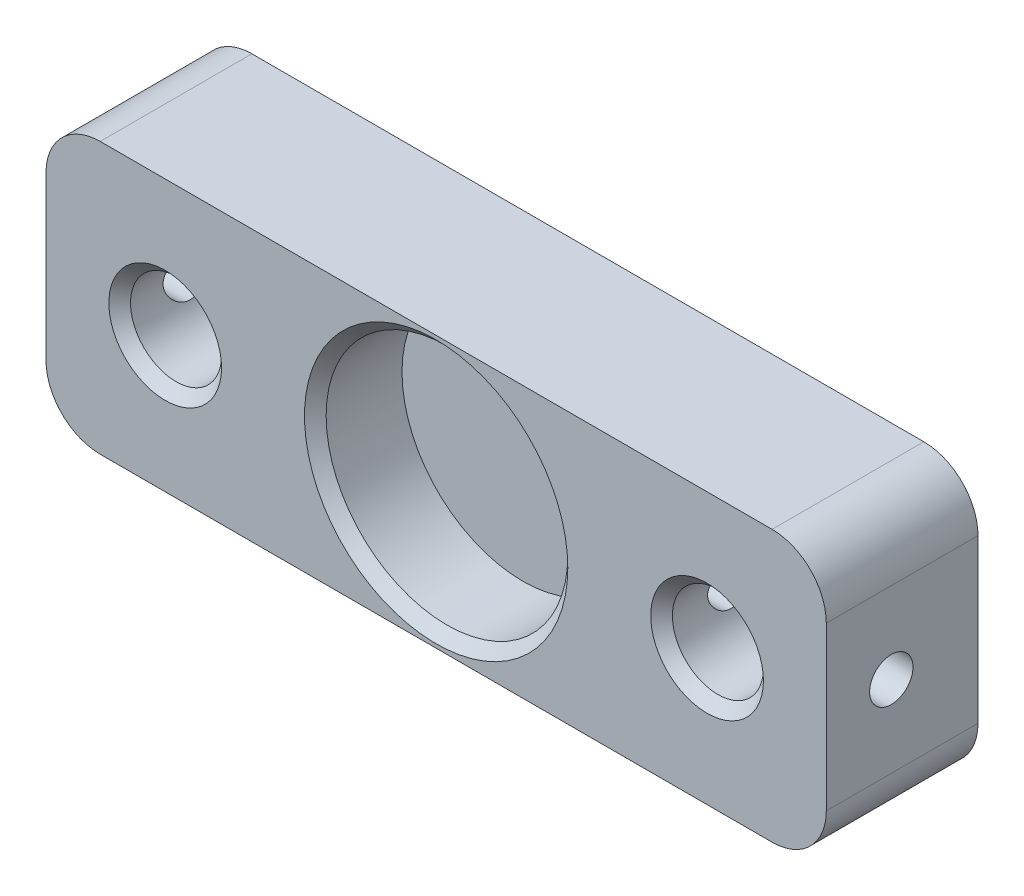
SolidWorks part; units mm, degrees
ref_plane "Płaszczyzna przednia" through (0, 0, 0) normal (0, 0, 1) x (1, 0, 0)
ref_plane "Płaszczyzna górna" through (0, 0, 0) normal (0, 1, 0) x (1, 0, 0)
ref_plane "Płaszczyzna prawa" through (0, 0, 0) normal (1, 0, 0) x (0, 0, -1)
sketch "Sketch1" plane through (0, 0, 0) normal (0, 0, 1) x (1, 0, 0)
  line L1 (-36, 12.5) -> (36, 12.5)
  line L2 (-36, 12.5) -> (-36, -12.5)
  line L3 (-36, -12.5) -> (36, -12.5)
  line L4 (36, 12.5) -> (36, -12.5)
  line L5 (-36, 12.5) -> (36, -12.5) construction
  line L6 (-36, -12.5) -> (36, 12.5) construction
  point P140 (0, 0)
  dimension "D1" = 72
  dimension "D2" = 25
extrude "Boss-Extrude1" add sketch "Sketch1" along normal blind 14
sketch "Sketch2" plane through (0, 0, 14) normal (0, 0, 1) x (1, 0, 0)
  circle A0 centre (0, 0) radius 11.15
  point P0 (0, 0)
  dimension "D1" = 22.3
extrude "Cut-Extrude1" cut sketch "Sketch2" against normal blind 8
sketch "Sketch3" plane through (0, 0, 14) normal (0, 0, 1) x (1, 0, 0)
  line L0 (-36, 0) -> (36, 0) construction
  line L1 (-36, 12.5) -> (-36, -12.5) construction
  line L2 (36, -12.5) -> (36, 12.5) construction
  circle A0 centre (-25, 0) radius 4.2
  circle A1 centre (25, 0) radius 4.2
  dimension "D3" = 8.4
  dimension "D4" = 8.4
  dimension "D1" = 25
  dimension "D2" = 25
extrude "Cut-Extrude2" cut sketch "Sketch3" against normal blind 12
sketch "Sketch4" plane through (-36, 0, 0) normal (-1, 0, 0) x (0, 0, 1)
  line L0 (0, 0) -> (14, 0) construction
  line L1 (0, 12.5) -> (0, -12.5) construction
  line L2 (14, 12.5) -> (14, -12.5) construction
  circle A0 centre (8, 0) radius 1.5
  point P6 (8, 0)
  dimension "D2" = 3
  dimension "D1" = 6
hole_wizard "Ø3.5 (3.5) Diameter Hole1" positions "Sketch4" profile "Sketch5" hole size "Ø3.5" standard "DIN"
sketch "Sketch5" plane through (-36, 0, 8) normal (0, 1, 0) x (0, 0, 1)
  line L0 (0, 0) -> (0, 21.0515)
  line L1 (0, 21.0515) -> (1.75, 20)
  line L2 (1.75, 20) -> (1.75, 0)
  line L5 (1.75, 0) -> (0, 0)
  line L10 (0, 21.0515) -> (-1.75, 20) construction
  line L11 (0, -6.35) -> (0, 107.95) construction
  dimension "Hole Dia." = 3.5
  dimension "Hole Depth" = 20
  dimension "Drill Angle" = 118
sketch "Sketch6" plane through (-36, 0, 0) normal (-1, 0, 0) x (0, 0, 1)
  circle A0 centre (8, 0) radius 2
  dimension "D1" = 4
extrude "Cut-Extrude3" cut sketch "Sketch6" against normal up to next
mirror "Mirror1" about plane through (0, 0, 0) normal (1, 0, 0) of "Ø3.5 (3.5) Diameter Hole1", "Cut-Extrude3"
fillet "Zaokrąglenie1" radius 5 4 edges at (-36, -12.5, 7) (36, -12.5, 7) (36, 12.5, 7) (-36, 12.5, 7)
chamfer "Sfazowanie1" distance 1 angle 45 3 edges at (-20.8, 0, 14) (11.15, 0, 14) (29.2, 0, 14)
